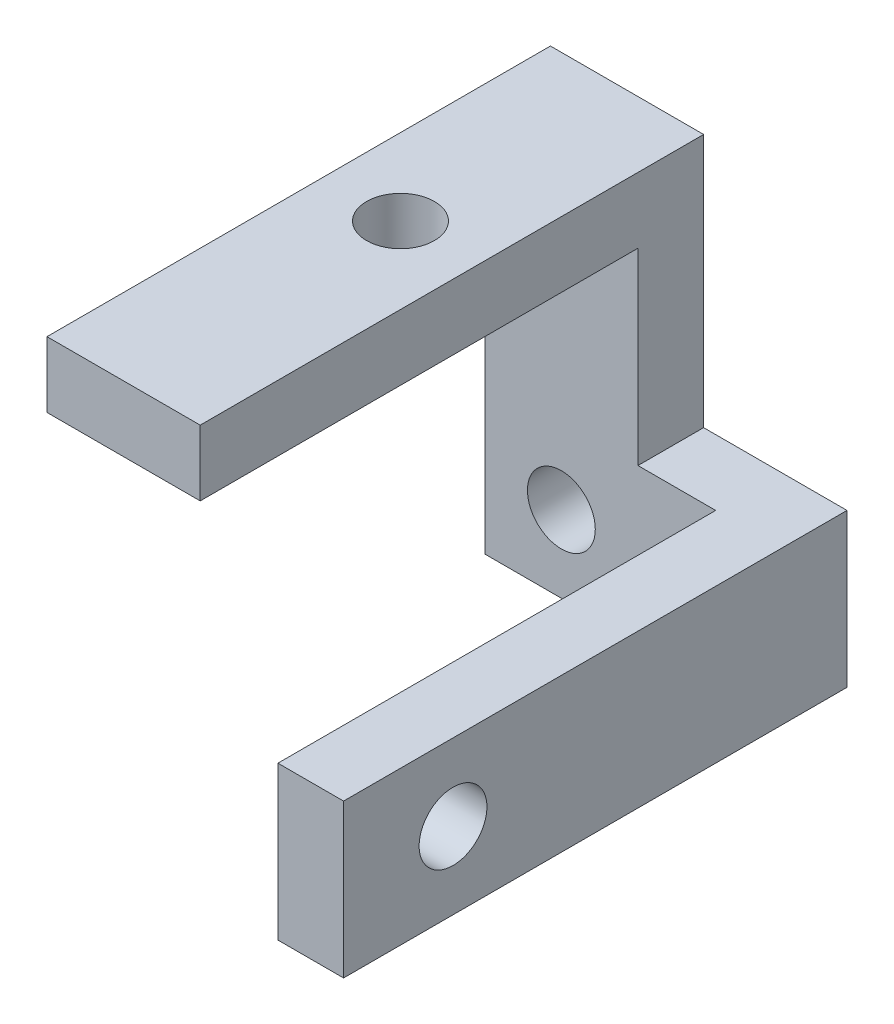
SolidWorks part; units mm, degrees
ref_plane "Plan de face" through (0, 0, 0) normal (0, 0, 1) x (1, 0, 0)
ref_plane "Plan de dessus" through (0, 0, 0) normal (0, 1, 0) x (1, 0, 0)
ref_plane "Plan de droite" through (0, 0, 0) normal (1, 0, 0) x (0, 0, -1)
sketch "Esquisse1" plane through (0, 0, 0) normal (0, 0, 1) x (1, 0, 0)
  line L1 (0, 0) -> (7, 0)
  line L2 (0, 0) -> (0, 18.6)
  line L3 (0, 18.6) -> (7, 18.6)
  line L4 (7, 0) -> (7, 18.6)
  line L5 (0, 7) -> (13.55, 7)
  line L6 (0, 7) -> (0, 0)
  line L7 (0, 0) -> (13.55, 0)
  line L8 (13.55, 7) -> (13.55, 0)
  dimension "D1" = 18.6
  dimension "D2" = 13.55
  dimension "D3" = 7
  dimension "D4" = 7
extrude "Boss.-Extru.1" add sketch "Esquisse1" along normal blind 3 contours L2 L5 L4 L3 | L5 L2 L1 L4 | L8 L5 L4 L7
sketch "Esquisse2" plane through (0, 0, 3) normal (0, 0, 1) x (1, 0, 0)
  line L0 (7, 7) -> (7, 18.6) construction
  line L1 (0, 18.6) -> (7, 18.6)
  line L2 (0, 18.6) -> (0, 15.6)
  line L3 (0, 15.6) -> (7, 15.6)
  line L4 (7, 18.6) -> (7, 15.6)
  dimension "D1" = 3
extrude "Boss.-Extru.2" add sketch "Esquisse2" along normal blind 20
sketch "Esquisse3" plane through (0, 0, 3) normal (0, 0, 1) x (1, 0, 0)
  line L0 (0, 0) -> (13.55, 0) construction
  line L1 (13.55, 7) -> (10.55, 7)
  line L2 (13.55, 7) -> (13.55, 0)
  line L3 (13.55, 0) -> (10.55, 0)
  line L4 (10.55, 7) -> (10.55, 0)
  dimension "D1" = 3
extrude "Boss.-Extru.3" add sketch "Esquisse3" along normal blind 20
sketch "Esquisse4" plane through (0, 15.6, 0) normal (0, -1, 0) x (1, 0, 0)
  line L0 (0, 23) -> (7, 23) construction
  line L1 (7, 23) -> (7, 3) construction
  circle A0 centre (3.5, 10.35) radius 1.55
  point P6 (0, 0)
  dimension "D1" = 3.1
  dimension "D2" = 12.65
  dimension "D3" = 3.5
sketch "Esquisse5" plane through (10.55, 0, 0) normal (-1, 0, 0) x (0, 0, 1)
  line L0 (23, 7) -> (3, 7) construction
  line L1 (23, 7) -> (23, 0) construction
  circle A0 centre (18, 3.5) radius 1.55
  dimension "D1" = 3.5
  dimension "D2" = 3.1
  dimension "D3" = 5
extrude "Enlèv. mat.-Extru.1" cut sketch "Esquisse4" against normal blind 20
extrude "Enlèv. mat.-Extru.2" cut sketch "Esquisse5" against normal blind 20
sketch "Esquisse6" plane through (0, 0, 3) normal (0, 0, 1) x (1, 0, 0)
  line L0 (0, 0) -> (0, 15.6) construction
  line L1 (0, 0) -> (10.55, 0) construction
  circle A0 centre (3.5, 3.5) radius 1.55
  dimension "D1" = 3.1
  dimension "D2" = 3.5
  dimension "D3" = 3.5
extrude "Enlèv. mat.-Extru.3" cut sketch "Esquisse6" against normal blind 20
